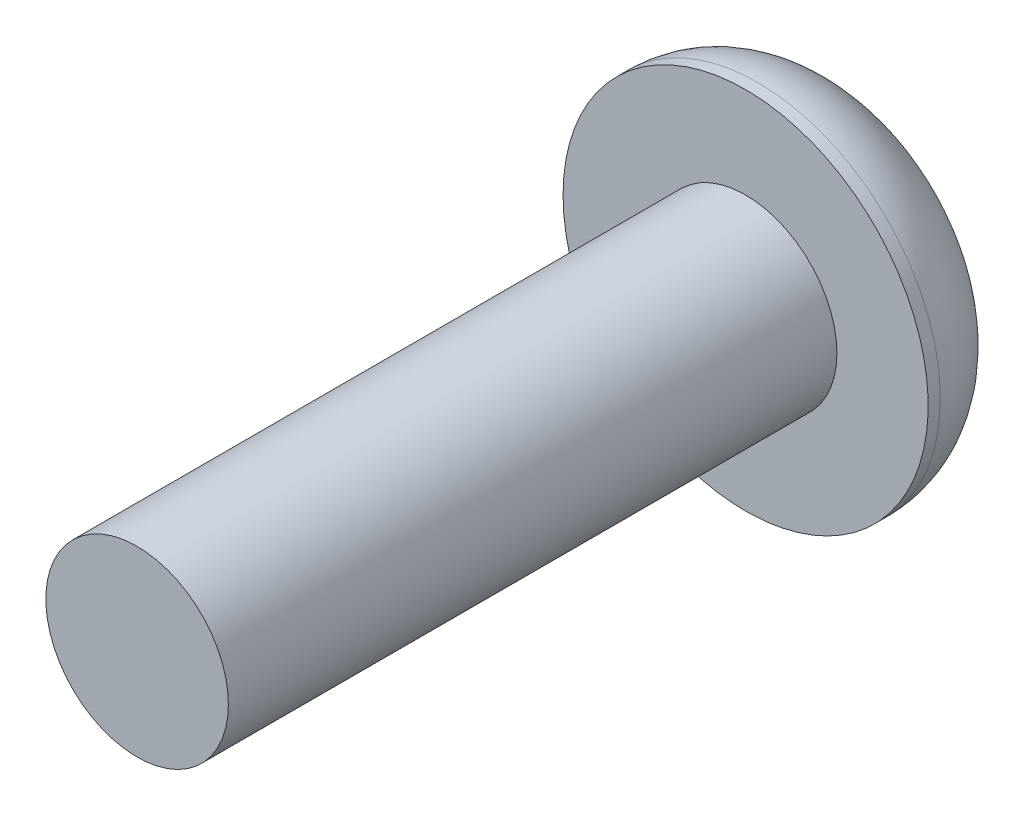
SolidWorks part; units mm, degrees
ref_plane "前视基准面" through (0, 0, 0) normal (0, 0, 1) x (1, 0, 0)
ref_plane "上视基准面" through (0, 0, 0) normal (0, 1, 0) x (1, 0, 0)
ref_plane "右视基准面" through (0, 0, 0) normal (1, 0, 0) x (0, 0, -1)
sketch "草图1" plane through (0, 0, 0) normal (0, 0, 1) x (1, 0, 0)
  circle A0 centre (0, 0) radius 1.5
extrude "凸台-拉伸1" add sketch "草图1" along normal blind 10
sketch "草图2" plane through (0, 0, 0) normal (0, 0, -1) x (-1, 0, 0)
  circle A0 centre (0, 0) radius 3
extrude "凸台-拉伸2" add sketch "草图2" along normal blind 1.7
fillet "圆角1" radius 1.5 1 edges at (-3, 0, -1.7)
